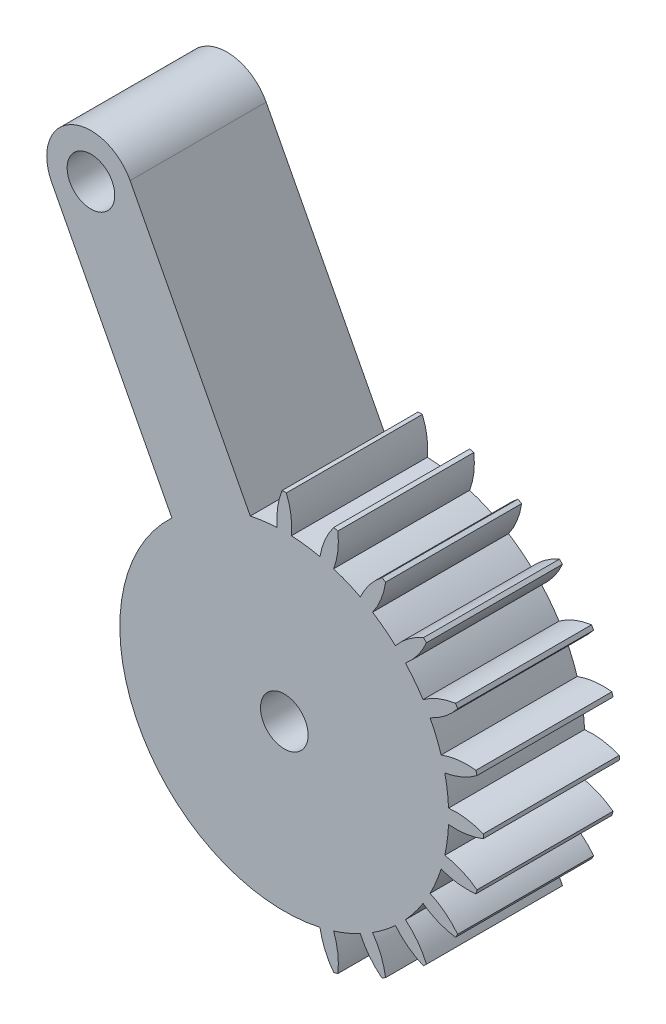
SolidWorks part; units mm, degrees
ref_plane "Front Plane" through (0, 0, 0) normal (0, 0, 1) x (1, 0, 0)
ref_plane "Top Plane" through (0, 0, 0) normal (0, 1, 0) x (1, 0, 0)
ref_plane "Right Plane" through (0, 0, 0) normal (1, 0, 0) x (0, 0, -1)
sketch "Sketch1" plane through (0, 0, 0) normal (0, 0, 1) x (1, 0, 0)
  line L0 (0, 0) -> (0, 16.3128) construction
  line L1 (0.155, 14.63) -> (-0.155, 14.63)
  line L2 (0, 0) -> (-14.3268, 27.4806) construction
  line L3 (3.9362, 14.0914) -> (3.6368, 14.1716)
  line L4 (7.4492, 12.5925) -> (7.1808, 12.7475)
  line L5 (10.4546, 10.2354) -> (10.2354, 10.4546)
  line L6 (12.7475, 7.1808) -> (12.5925, 7.4492)
  line L7 (14.1716, 3.6368) -> (14.0914, 3.9362)
  line L8 (14.63, -0.155) -> (14.63, 0.155)
  line L9 (14.0914, -3.9362) -> (14.1716, -3.6368)
  line L10 (12.5925, -7.4492) -> (12.7475, -7.1808)
  line L11 (10.2354, -10.4546) -> (10.4546, -10.2354)
  line L12 (7.1808, -12.7475) -> (7.4492, -12.5925)
  line L13 (3.6368, -14.1716) -> (3.9362, -14.0914)
  line L14 (0, 0) -> (0.52, 12.0788) construction
  line L15 (0, 0) -> (3.6285, 11.5327) construction
  line L16 (-2.5015, 11.8284) -> (-11.3335, 28.7694)
  line L17 (-8.2652, 8.8235) -> (-17.0973, 25.7645)
  circle A0 centre (0, 0) radius 1.75
  arc A1 (-8.2652, 8.8235) -> (2.6239, -11.8018) centre (0, 0) ccw
  arc A2 (-11.3335, 28.7694) -> (-17.0973, 25.7645) centre (-14.2154, 27.2669) ccw
  circle A3 centre (-14.2154, 27.2669) radius 1.75
  arc A4 (-0.155, 14.63) -> (-0.52, 12.0788) centre (4.8536, 12.6117) ccw
  arc A5 (0.155, 14.63) -> (0.52, 12.0788) centre (-4.8536, 12.6117) cw
  arc A6 (3.9362, 14.0914) -> (3.6285, 11.5327) centre (-1.4241, 13.4382) cw
  arc A7 (3.6368, 14.1716) -> (2.6239, 11.8018) centre (7.9524, 10.9258) ccw
  arc A8 (7.4492, 12.5925) -> (6.4897, 10.2006) centre (2.1025, 13.3489) cw
  arc A9 (7.1808, 12.7475) -> (5.5891, 10.7206) centre (10.5092, 8.4952) ccw
  arc A10 (10.4546, 10.2354) -> (8.9087, 8.1733) centre (5.4858, 12.3499) cw
  arc A11 (10.2354, 10.4546) -> (8.1733, 8.9087) centre (12.3499, 5.4858) ccw
  arc A12 (12.7475, 7.1808) -> (10.7206, 5.5891) centre (8.4952, 10.5092) cw
  arc A13 (12.5925, 7.4492) -> (10.2006, 6.4897) centre (13.3489, 2.1025) ccw
  arc A14 (14.1716, 3.6368) -> (11.8018, 2.6239) centre (10.9258, 7.9524) cw
  arc A15 (14.0914, 3.9362) -> (11.5327, 3.6285) centre (13.4382, -1.4241) ccw
  arc A16 (14.63, -0.155) -> (12.0788, -0.52) centre (12.6117, 4.8536) cw
  arc A17 (14.63, 0.155) -> (12.0788, 0.52) centre (12.6117, -4.8536) ccw
  arc A18 (14.0914, -3.9362) -> (11.5327, -3.6285) centre (13.4382, 1.4241) cw
  arc A19 (14.1716, -3.6368) -> (11.8018, -2.6239) centre (10.9258, -7.9524) ccw
  arc A20 (12.5925, -7.4492) -> (10.2006, -6.4897) centre (13.3489, -2.1025) cw
  arc A21 (12.7475, -7.1808) -> (10.7206, -5.5891) centre (8.4952, -10.5092) ccw
  arc A22 (10.2354, -10.4546) -> (8.1733, -8.9087) centre (12.3499, -5.4858) cw
  arc A23 (10.4546, -10.2354) -> (8.9087, -8.1733) centre (5.4858, -12.3499) ccw
  arc A24 (7.1808, -12.7475) -> (5.5891, -10.7206) centre (10.5092, -8.4952) cw
  arc A25 (7.4492, -12.5925) -> (6.4897, -10.2006) centre (2.1025, -13.3489) ccw
  arc A26 (3.6368, -14.1716) -> (2.6239, -11.8018) centre (7.9524, -10.9258) cw
  arc A27 (3.9362, -14.0914) -> (3.6285, -11.5327) centre (-1.4241, -13.4382) ccw
  arc A28 (-0.52, 12.0788) -> (-2.5015, 11.8284) centre (0, 0) ccw
  arc A29 (2.6239, 11.8018) -> (0.52, 12.0788) centre (0, 0) ccw
  arc A30 (5.5891, 10.7206) -> (3.6285, 11.5327) centre (0, 0) ccw
  arc A31 (8.1733, 8.9087) -> (6.4897, 10.2006) centre (0, 0) ccw
  arc A32 (10.2006, 6.4897) -> (8.9087, 8.1733) centre (0, 0) ccw
  arc A33 (11.5327, 3.6285) -> (10.7206, 5.5891) centre (0, 0) ccw
  arc A34 (12.0788, 0.52) -> (11.8018, 2.6239) centre (0, 0) ccw
  arc A35 (11.8018, -2.6239) -> (12.0788, -0.52) centre (0, 0) ccw
  arc A36 (10.7206, -5.5891) -> (11.5327, -3.6285) centre (0, 0) ccw
  arc A37 (8.9087, -8.1733) -> (10.2006, -6.4897) centre (0, 0) ccw
  arc A38 (6.4897, -10.2006) -> (8.1733, -8.9087) centre (0, 0) ccw
  arc A39 (3.6285, -11.5327) -> (5.5891, -10.7206) centre (0, 0) ccw
  point P13 (0, 14.63)
  dimension "D1" = 3.5
  dimension "D2" = 24.18
  dimension "D3" = 6.5
  dimension "D4" = 3.5
  dimension "D8" = 5.4
  dimension "D5" = 45
  dimension "D6" = 0.31
  dimension "D7" = 1.04
  dimension "D9" = 14.63
  dimension "D11" = 15
  dimension "D12" = 30.75
  dimension "D10" = 12
extrude "Boss-Extrude1" add sketch "Sketch1" along normal blind 10
